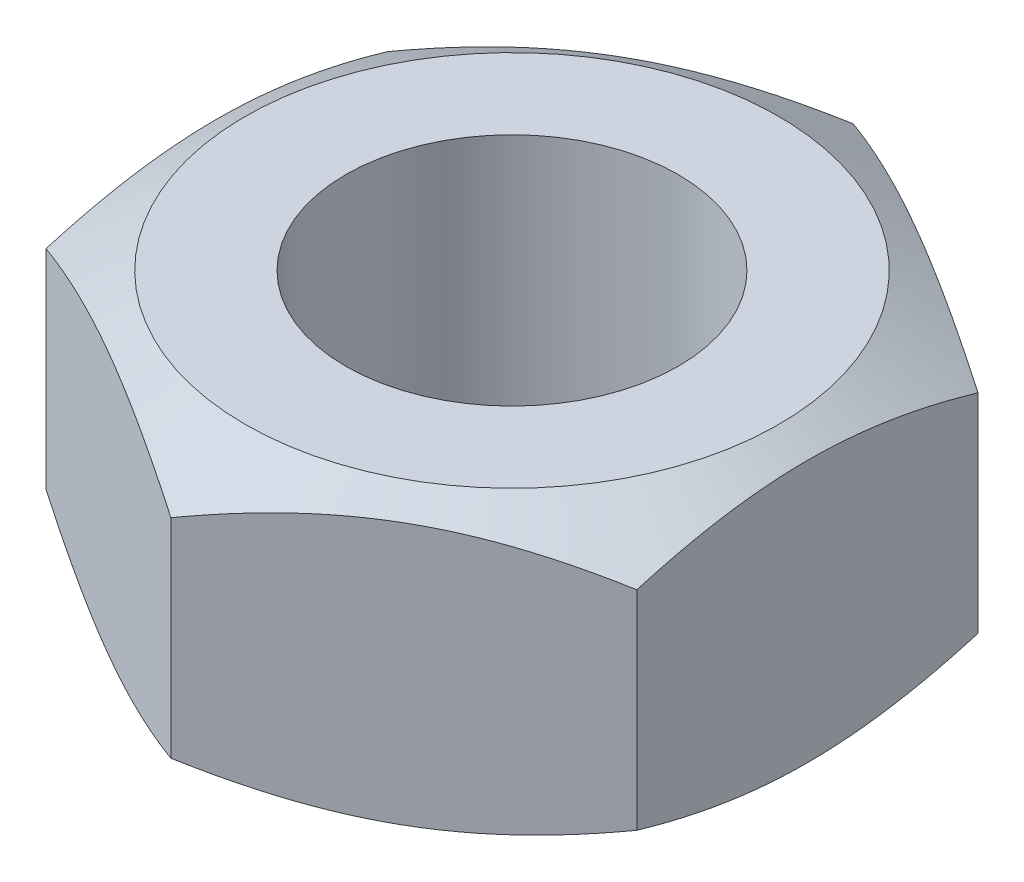
SolidWorks part; units mm, degrees
ref_plane "Front Plane" through (0, 0, 0) normal (0, 0, 1) x (1, 0, 0)
ref_plane "Top Plane" through (0, 0, 0) normal (0, 1, 0) x (1, 0, 0)
ref_plane "Right Plane" through (0, 0, 0) normal (1, 0, 0) x (0, 0, -1)
sketch "Sketch1" plane through (0, 0, 0) normal (0, 1, 0) x (1, 0, 0)
  line L1 (0, 4.6188) -> (-4, 2.3094)
  line L2 (-4, 2.3094) -> (-4, -2.3094)
  line L3 (-4, -2.3094) -> (0, -4.6188)
  line L4 (0, -4.6188) -> (4, -2.3094)
  line L5 (4, -2.3094) -> (4, 2.3094)
  line L6 (4, 2.3094) -> (0, 4.6188)
  circle A0 centre (0, 0) radius 4 construction
  circle A1 centre (0, 0) radius 2.25
  dimension "D1" = 4.5
  dimension "D2" = 8
extrude "Boss-Extrude1" add sketch "Sketch1" along normal blind 4
sketch "Sketch2" plane through (0, 0, 0) normal (1, 0, 0) x (0, 0, -1)
  line L0 (-4.6188, 2) -> (4.6188, 2) construction
  line L1 (-4.6188, 4) -> (-4.6188, 0) construction
  line L2 (4.6188, 4) -> (4.6188, 0) construction
  line L3 (-5.0755, 3.1429) -> (-2.4447, 4.6838)
  line L4 (-2.4447, 4.6838) -> (-4.7317, 4.8386)
  line L5 (-4.7317, 4.8386) -> (-5.0755, 3.1429)
  line L6 (-4.7317, -0.8386) -> (-5.0755, 0.8571)
  line L7 (-2.4447, -0.6838) -> (-4.7317, -0.8386)
  line L8 (-5.0755, 0.8571) -> (-2.4447, -0.6838)
  line L9 (0, 4.2123) -> (0, -1.8351) construction
revolve "Cut-Revolve1" cut sketch "Sketch2" angle 360 about L9
